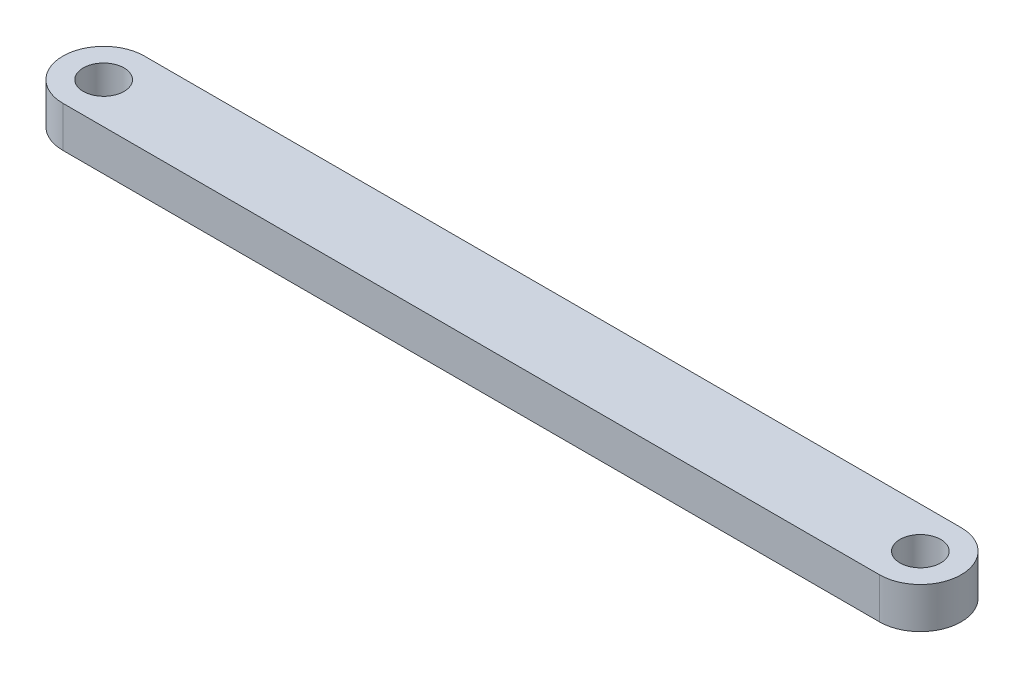
SolidWorks part; units mm, degrees
ref_plane "정면" through (0, 0, 0) normal (0, 0, 1) x (1, 0, 0)
ref_plane "윗면" through (0, 0, 0) normal (0, 1, 0) x (1, 0, 0)
ref_plane "우측면" through (0, 0, 0) normal (1, 0, 0) x (0, 0, -1)
sketch "스케치1" plane through (0, 0, 0) normal (0, 1, 0) x (1, 0, 0)
  line L0 (0, 0) -> (100, 0) construction
  line L1 (0, 5) -> (100, 5)
  line L2 (0, -5) -> (100, -5)
  arc A0 (0, 5) -> (0, -5) centre (0, 0) ccw
  arc A1 (100, -5) -> (100, 5) centre (100, 0) ccw
  point P3 (50, 0)
  dimension "D1" = 5
  dimension "D2" = 100
extrude "보스-돌출1" add sketch "스케치1" along normal blind 5
sketch "스케치2" plane through (0, 5, 0) normal (0, 1, 0) x (1, 0, 0)
  circle A0 centre (0, 0) radius 2.5
  circle A1 centre (100, 0) radius 2.5
  dimension "D1" = 5
  dimension "D2" = 5
extrude "컷-돌출1" cut sketch "스케치2" against normal blind 5 contours A0 | A1
